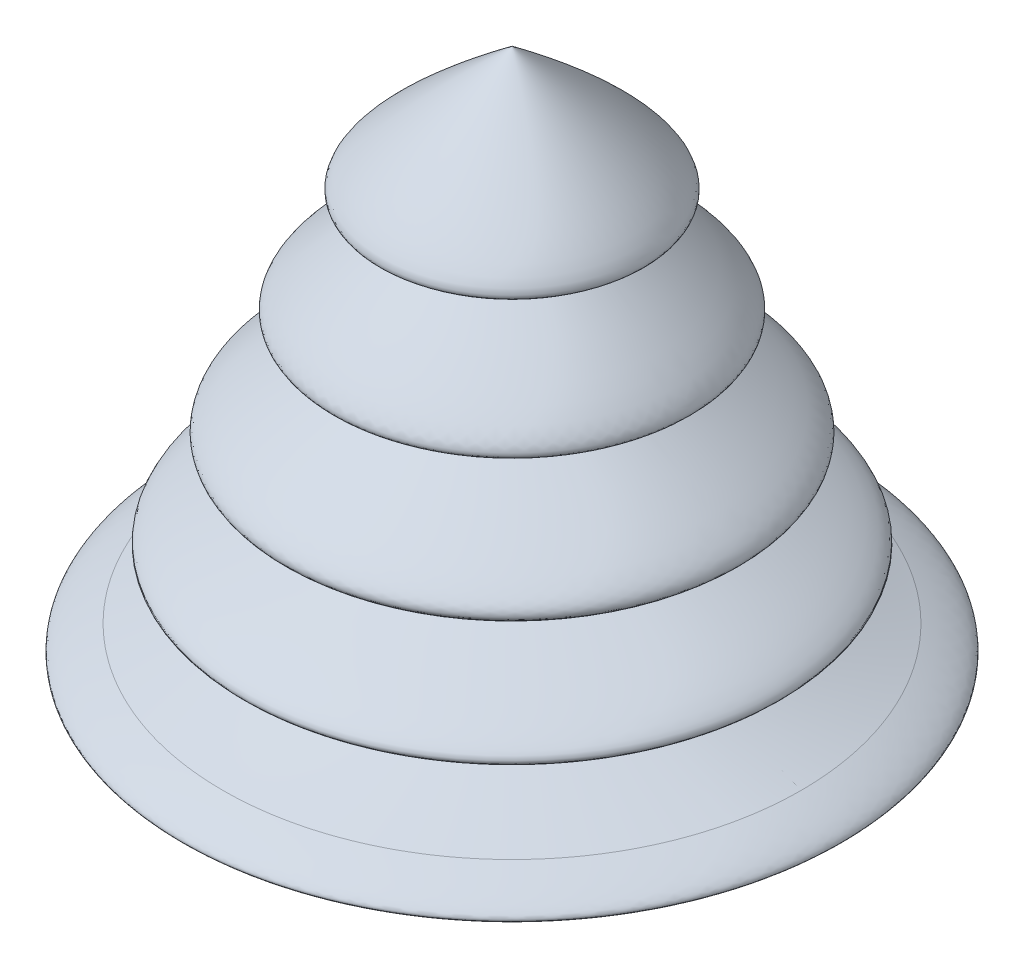
SolidWorks part; units mm, degrees
ref_plane "Płaszczyzna przednia" through (0, 0, 0) normal (0, 0, 1) x (1, 0, 0)
ref_plane "Płaszczyzna górna" through (0, 0, 0) normal (0, 1, 0) x (1, 0, 0)
ref_plane "Płaszczyzna prawa" through (0, 0, 0) normal (1, 0, 0) x (0, 0, -1)
sketch "Szkic1" plane through (0, 0, 0) normal (0, 0, 1) x (1, 0, 0)
  line L0 (0, -7.6377) -> (0, 79.9946) construction
  line L2 (0, -7.6377) -> (0, 79.9946)
  line L3 (0, -7.6377) -> (53.2695, -7.6377)
  spline S0 degree 3 poles (0, 79.9946) (45.7837, 44.0412) (-16.6521, 77.4999) (43.3218, 35.918) (-1.1761, 47.4161) (56.2142, 19.2829) (6.4753, 25.5387) (29.6517, 17.327) (53.8264, 6.0311) (18.7722, 8.337) (47.9367, -2.9039) (47.9367, -2.9039) knots 0 0 0 0 0.185334 0.281542 0.356051 0.476894 0.611779 0.765991 0.898028 0.921429 1 1 1 1
  spline S1 degree 3 poles (47.9367, -2.9039) (54.4245, -5.6074) (56.2021, -7.1853) (53.2695, -7.6377) knots 0 0 0 0 0.713312 0.713312 0.713312 0.713312
  point P4 (54.6126, -7.0308)
  point P8 (48.1795, -3.9963)
  point P10 (47.4512, -7.6377)
  point P12 (47.9367, -2.9039)
  dimension "D2" = 202.8406
  dimension "D3" = 9.6235
  dimension "D1" = 53.2695
revolve "Obrót1" add sketch "Szkic1" angle 360 about L0
sketch "Szkic2" plane through (0, -7.6377, 0) normal (0, -1, 0) x (1, 0, 0)
  circle A0 centre (0, 0) radius 13
  dimension "D1" = 26
extrude "Dodanie-wyciągnięcie1" add sketch "Szkic2" along normal blind 10 draft 30 draft outward yes
